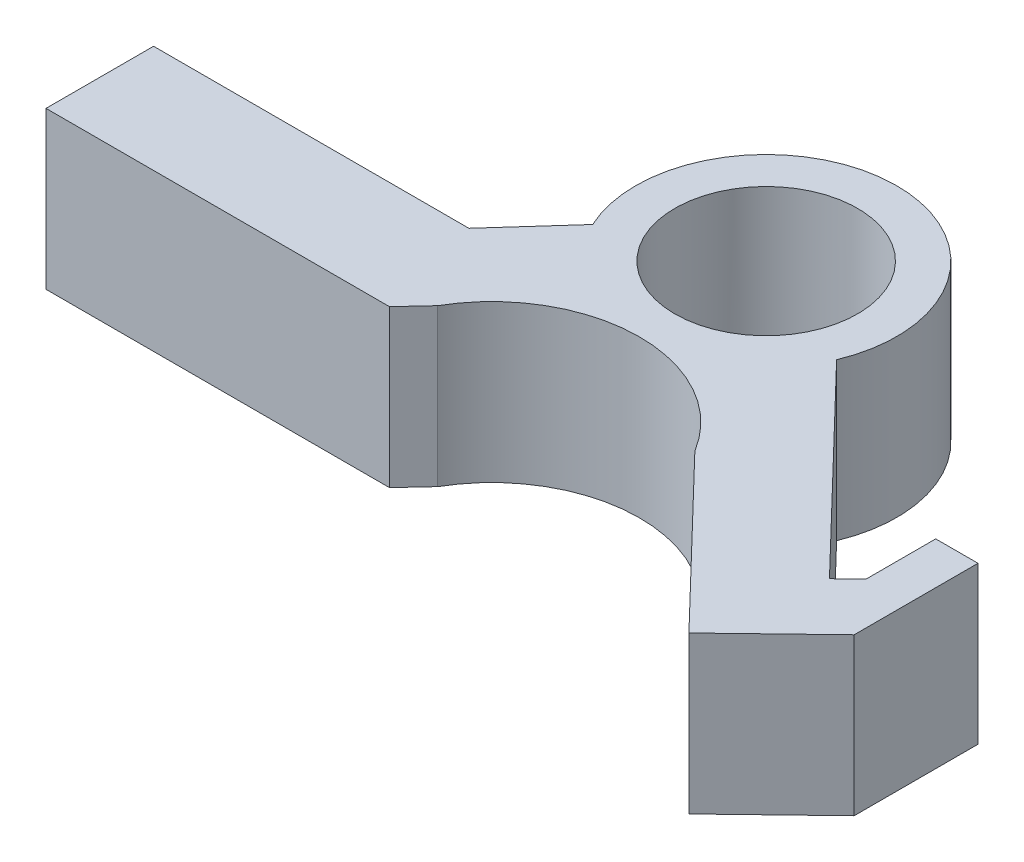
SolidWorks part; units mm, degrees
ref_plane "Спереди" through (0, 0, 0) normal (0, 0, 1) x (1, 0, 0)
ref_plane "Сверху" through (0, 0, 0) normal (0, 1, 0) x (1, 0, 0)
ref_plane "Справа" through (0, 0, 0) normal (1, 0, 0) x (0, 0, -1)
other "Configuration Table"
sketch "Эскиз1" plane through (0, 0, 0) normal (0, 1, 0) x (1, 0, 0)
  line L1 (1.3039, 4.9814) -> (2.4258, 6.2292)
  line L2 (7.0014, 6.3217) -> (10.5626, 2.6235)
  line L3 (10.5626, 2.6235) -> (10.9196, 2.9672)
  line L5 (11.7286, 1.9308) -> (10.1172, 0.3791)
  line L6 (10.1172, 0.3791) -> (7.1574, 3.4527)
  line L7 (2.2872, 3.4002) -> (1.8427, 2.9222)
  line L12 (11.7286, 3.2527) -> (11.7286, 4.3008)
  line L13 (11.7286, 4.3008) -> (10.9196, 4.3008)
  line L14 (10.9196, 4.3008) -> (10.9196, 2.9672)
  line L15 (11.7286, 3.2527) -> (11.7286, 1.9308)
  line L17 (-0.5475, 2.9222) -> (1.8427, 2.9222)
  line L18 (-4.7311, 4.9814) -> (1.3039, 4.9814)
  line L19 (-4.7311, 4.9814) -> (-4.7311, 2.9222)
  line L20 (-4.7311, 2.9222) -> (-0.5475, 2.9222)
  arc A0 (2.2872, 3.4002) -> (7.1574, 3.4527) centre (4.7379, 1.9847) cw
  arc A3 (7.0014, 6.3217) -> (2.4258, 6.2292) centre (4.6932, 7.2822) ccw
  dimension "D2" = 1.3335
extrude "Бобышка-Вытянуть1" add sketch "Эскиз1" along normal blind 3
sketch "Эскиз3" plane through (0, 3, 0) normal (0, 1, 0) x (1, 0, 0)
  circle A0 centre (4.6932, 7.2822) radius 1.75
  dimension "D1" = 3.5
extrude "Вырез-Вытянуть1" cut sketch "Эскиз3" against normal blind 10
